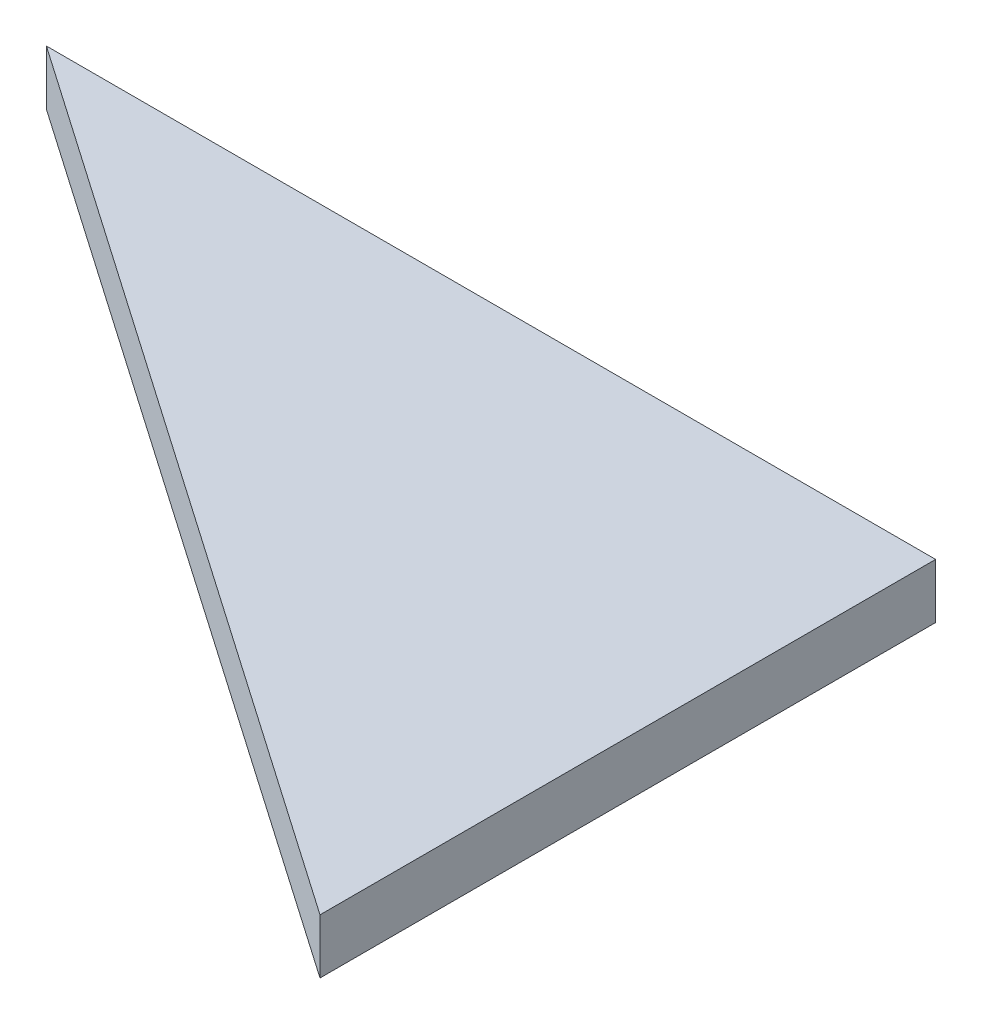
SolidWorks part; units mm, degrees
ref_plane "Front Plane" through (0, 0, 0) normal (0, 0, 1) x (1, 0, 0)
ref_plane "Top Plane" through (0, 0, 0) normal (0, 1, 0) x (1, 0, 0)
ref_plane "Right Plane" through (0, 0, 0) normal (1, 0, 0) x (0, 0, -1)
sketch "Sketch1" plane through (0, 0, 0) normal (0, 1, 0) x (1, 0, 0)
  line L0 (0, 0) -> (0, -45)
  line L1 (0, -45) -> (-65, 0)
  line L2 (-65, 0) -> (0, 0)
  dimension "D1" = 65
  dimension "D2" = 45
  dimension "D3" = 270
extrude "Boss-Extrude1" add sketch "Sketch1" along normal blind 4
